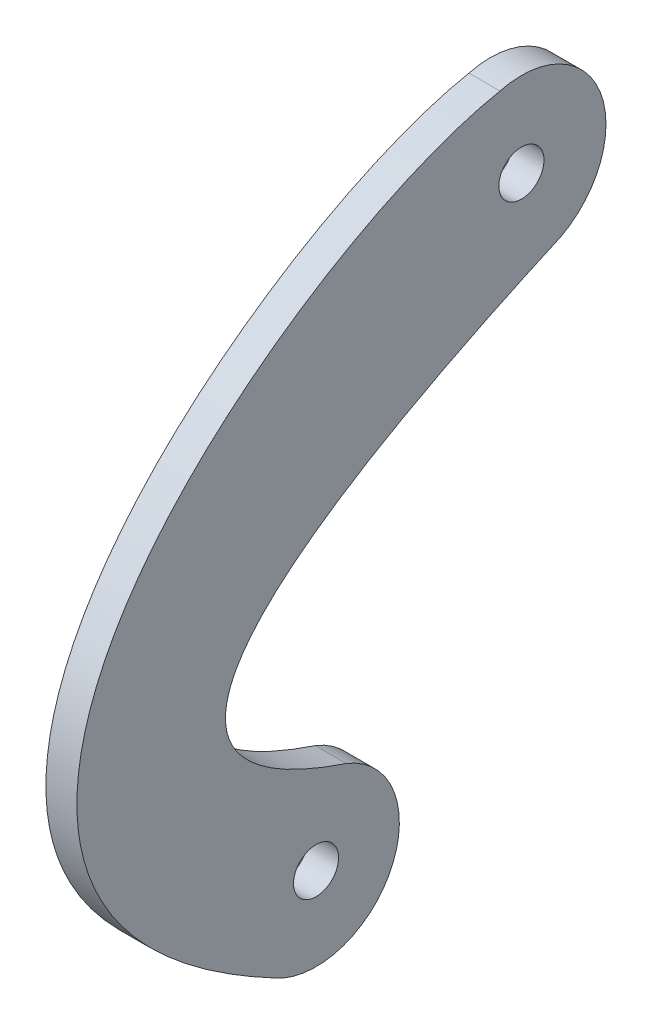
SolidWorks part; units mm, degrees
ref_plane "Спереди" through (0, 0, 0) normal (0, 0, 1) x (1, 0, 0)
ref_plane "Сверху" through (0, 0, 0) normal (0, 1, 0) x (1, 0, 0)
ref_plane "Справа" through (0, 0, 0) normal (1, 0, 0) x (0, 0, -1)
sketch "Эскиз1" plane through (0, 0, 0) normal (1, 0, 0) x (0, 0, -1)
  arc A0 (-9.5409, -26.3986) -> (-20.3751, 1.3614) centre (-16.5715, -13.1483) ccw
  circle A1 centre (-16.5715, -13.1483) radius 4
  circle A2 centre (-52.9963, -102.0706) radius 4
  arc A3 (-60.4239, -114.8457) -> (-47.6377, -88.2989) centre (-52.9963, -102.0706) ccw
  spline S0 degree 3 poles (-20.3751, 1.3614) (-59.7443, -6.1956) (-142.4352, -71.3892) (-60.4239, -114.8457) knots 0 0 0 0 1 1 1 1
  spline S1 degree 3 poles (-9.5409, -26.3986) (-57.7615, -47.9257) (-93.9277, -72.9022) (-47.6377, -88.2989) knots 0 0 0 0 1 1 1 1
extrude "Вытянуть1" add sketch "Эскиз1" along normal blind 5.5
